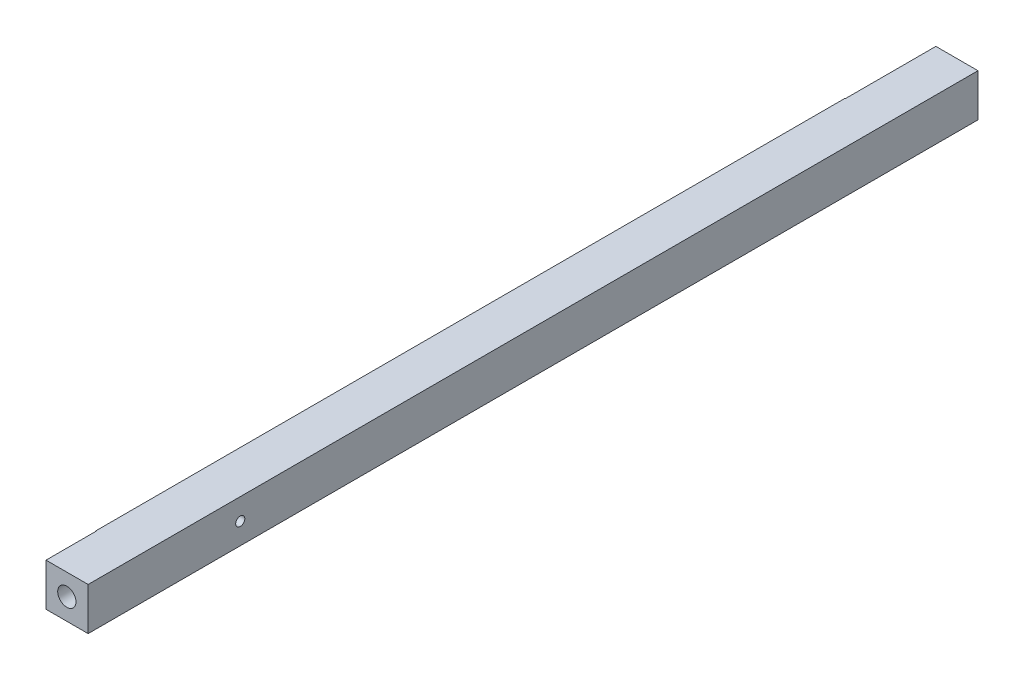
SolidWorks part; units mm, degrees
ref_plane "Ön Düzlem" through (0, 0, 0) normal (0, 0, 1) x (1, 0, 0)
ref_plane "Üst Düzlem" through (0, 0, 0) normal (0, 1, 0) x (1, 0, 0)
ref_plane "Sağ Düzlem" through (0, 0, 0) normal (1, 0, 0) x (0, 0, -1)
sketch "Çizim1" plane through (0, 0, 0) normal (0, 0, 1) x (1, 0, 0)
  line L1 (-14, -14) -> (14, -14)
  line L2 (-14, -14) -> (-14, 14)
  line L3 (-14, 14) -> (14, 14)
  line L4 (14, -14) -> (14, 14)
  line L5 (-14, -14) -> (14, 14) construction
  line L6 (-14, 14) -> (14, -14) construction
  point P0 (0, 0)
  dimension "D1" = 28
  dimension "D2" = 28
extrude "Yükseklik-Ekstrüzyon1" add sketch "Çizim1" along normal blind 585
sketch "Çizim2" plane through (0, 0, 585) normal (0, 0, 1) x (1, 0, 0)
  circle A0 centre (0, 0) radius 6
  dimension "D1" = 12
extrude "Kes-Ekstrüzyon1" cut sketch "Çizim2" against normal blind 60
sketch "Sketch1" plane through (0, 0, 0) normal (0, 0, -1) x (-1, 0, 0)
  line L0 (-14, -14) -> (-14, 14) construction
  line L1 (7, 7) -> (-7, 7) construction
  line L2 (7, 7) -> (7, -7) construction
  line L3 (7, -7) -> (-7, -7) construction
  line L4 (-7, 7) -> (-7, -7) construction
  line L5 (7, 7) -> (-7, -7) construction
  line L6 (7, -7) -> (-7, 7) construction
  line L7 (-14, 14) -> (14, 14) construction
  line L8 (14, 14) -> (14, -14) construction
  line L9 (14, -14) -> (-14, -14) construction
  circle A2 centre (-7, -7) radius 3
  circle A3 centre (7, 7) radius 3
  point P0 (0, 0)
  point P12 (7, -7)
  dimension "D3" = 6
  dimension "D4" = 6
  dimension "D1" = 7
  dimension "D2" = 7
extrude "Cut-Extrude1" cut sketch "Sketch1" against normal blind 10
sketch "Sketch2" plane through (-14, 0, 0) normal (-1, 0, 0) x (0, 0, 1)
  line L0 (585, 14) -> (585, -14) construction
  line L1 (585, 14) -> (0, 14) construction
  circle A0 centre (485, 0) radius 3
  dimension "D1" = 100
  dimension "D2" = 6
  dimension "D3" = 14
extrude "Cut-Extrude2" cut sketch "Sketch2" against normal through all
sketch "Sketch3" plane through (-14, 0, 0) normal (-1, 0, 0) x (0, 0, 1)
  circle A0 centre (485, 0) radius 4.25
  dimension "D1" = 8.5
extrude "Cut-Extrude3" cut sketch "Sketch3" against normal blind 6
sketch "Sketch4" plane through (-14, 0, 0) normal (-1, 0, 0) x (0, 0, 1)
  line L0 (585, 14) -> (585, -14) construction
  line L1 (552, -35.7953) -> (631.5612, -35.7953)
  line L2 (552, -35.7953) -> (552, 48.4228)
  line L3 (552, 48.4228) -> (631.5612, 48.4228)
  line L4 (631.5612, -35.7953) -> (631.5612, 48.4228)
  line L5 (-85.2129, -88.5869) -> (59.5, -88.5869)
  line L6 (-85.2129, -88.5869) -> (-85.2129, 117.8826)
  line L7 (-85.2129, 117.8826) -> (59.5, 117.8826)
  line L8 (59.5, -88.5869) -> (59.5, 117.8826)
  line L9 (0, 14) -> (0, -14) construction
  dimension "D1" = 33
  dimension "D2" = 59.5
extrude "Cut-Extrude4" cut sketch "Sketch4" against normal blind 0.3
